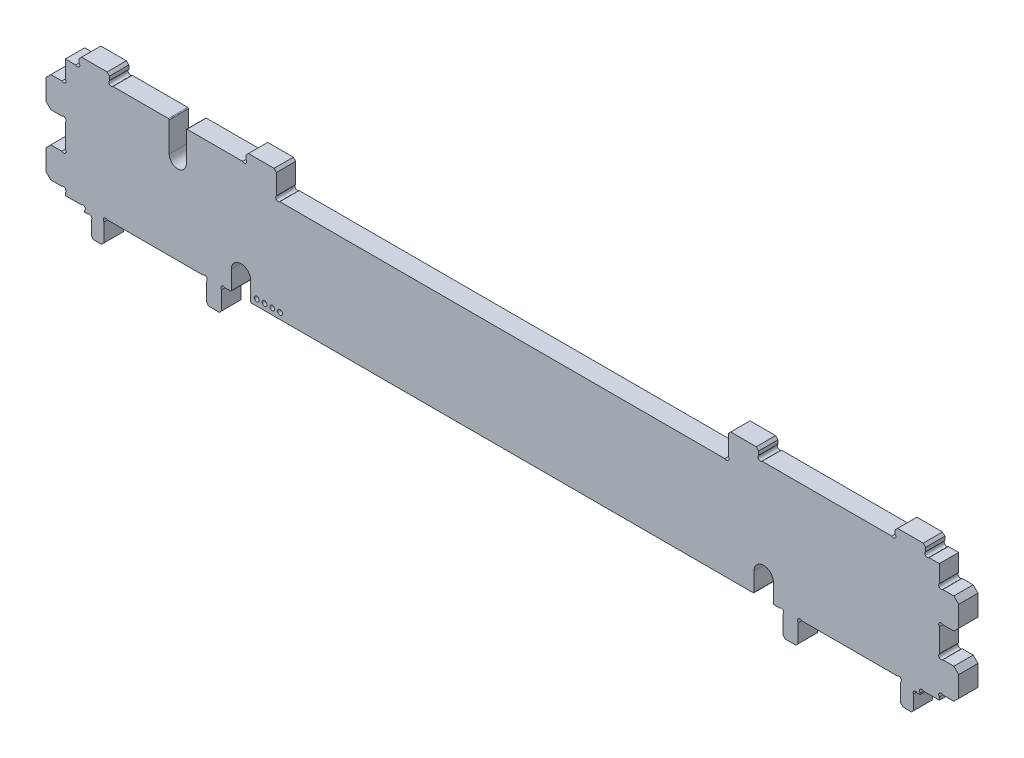
SolidWorks part; units mm, degrees
material "PVC Rigid"
ref_plane "Front Plane" through (0, 0, 0) normal (0, 0, 1) x (1, 0, 0)
ref_plane "Top Plane" through (0, 0, 0) normal (0, 1, 0) x (1, 0, 0)
ref_plane "Right Plane" through (0, 0, 0) normal (1, 0, 0) x (0, 0, -1)
sketch "Model" plane through (0, 0, 0) normal (0, 0, 1) x (1, 0, 0)
  line L0 (138.1552, -67.6125) -> (138.949, -66.8188)
  line L1 (134.6215, -66.8188) -> (135.4153, -67.6125)
  line L2 (100.1328, -67.6125) -> (100.9265, -66.8188)
  line L3 (95.9265, -66.8188) -> (96.7203, -67.6125)
  line L4 (-89.3772, -67.6125) -> (-88.5835, -66.8188)
  line L5 (-93.5835, -66.8188) -> (-92.7897, -67.6125)
  line L6 (-128.0722, -67.6125) -> (-127.2785, -66.8188)
  line L7 (-131.5077, -66.8188) -> (-130.7139, -67.6125)
  line L8 (-146.3285, -56.025) -> (-144.741, -57.6125)
  line L9 (-144.741, -47.6125) -> (-146.3285, -49.2)
  line L10 (-146.3285, -36.025) -> (-144.741, -37.6125)
  line L11 (-144.741, -27.6125) -> (-146.3285, -29.2)
  line L12 (-134.6597, -17.6125) -> (-135.4535, -18.4063)
  line L13 (-125.4535, -18.4063) -> (-126.2472, -17.6125)
  line L14 (-79.7957, -17.6125) -> (-80.5895, -18.4063)
  line L15 (-70.5895, -18.4063) -> (-71.3832, -17.6125)
  line L16 (-69.4669, -26.1597) -> (76.81, -26.1597)
  line L17 (78.7263, -17.6125) -> (77.9325, -18.4063)
  line L18 (87.9325, -18.4063) -> (87.1388, -17.6125)
  line L19 (133.5903, -17.6125) -> (132.7965, -18.4063)
  line L20 (142.7965, -18.4063) -> (142.0028, -17.6125)
  line L21 (153.6715, -29.2) -> (152.084, -27.6125)
  line L22 (152.084, -37.6125) -> (153.6715, -36.025)
  line L23 (153.6715, -49.2) -> (152.084, -47.6125)
  line L24 (152.084, -57.6125) -> (153.6715, -56.025)
  line L25 (102.0491, -59.6877) -> (133.499, -59.6877)
  line L26 (100.9265, -66.8188) -> (100.9265, -60.8103)
  line L27 (96.7203, -67.6125) -> (100.1328, -67.6125)
  line L28 (95.9265, -60.8103) -> (95.9265, -66.8188)
  line L29 (-87.4609, -59.6877) -> (94.804, -59.6877)
  line L30 (-88.5835, -66.8188) -> (-88.5835, -60.8103)
  line L31 (-92.7897, -67.6125) -> (-89.3772, -67.6125)
  line L32 (-93.5835, -60.8103) -> (-93.5835, -66.8188)
  line L33 (-126.1559, -59.6877) -> (-94.706, -59.6877)
  line L34 (-127.2785, -66.8188) -> (-127.2785, -60.8103)
  line L35 (-130.7139, -67.6125) -> (-128.0722, -67.6125)
  line L36 (-131.5077, -62.3851) -> (-131.5077, -66.8188)
  line L37 (-133.6285, -61.2625) -> (-132.6302, -61.2625)
  line L38 (-133.6285, -60.8103) -> (-133.6285, -61.2625)
  line L39 (-139.9785, -59.6877) -> (-134.751, -59.6877)
  line L40 (-139.9785, -58.7351) -> (-139.9785, -59.6877)
  line L41 (-144.741, -57.6125) -> (-141.101, -57.6125)
  line L42 (-146.3285, -49.2) -> (-146.3285, -56.025)
  line L43 (-141.101, -47.6125) -> (-144.741, -47.6125)
  line L44 (-139.9785, -38.7351) -> (-139.9785, -46.49)
  line L45 (-144.741, -37.6125) -> (-141.101, -37.6125)
  line L46 (-146.3285, -29.2) -> (-146.3285, -36.025)
  line L47 (-141.101, -27.6125) -> (-144.741, -27.6125)
  line L48 (-139.9785, -20.7875) -> (-139.9785, -26.49)
  line L49 (-136.576, -20.7875) -> (-139.9785, -20.7875)
  line L50 (-135.4535, -18.4063) -> (-135.4535, -19.665)
  line L51 (-126.2472, -17.6125) -> (-134.6597, -17.6125)
  line L52 (-125.4535, -19.665) -> (-125.4535, -18.4063)
  line L53 (-105.5215, -20.7875) -> (-124.3309, -20.7875)
  line L54 (-105.5215, -29.665) -> (-105.5215, -20.7875)
  line L55 (-101.644, -30.7875) -> (-104.3989, -30.7875)
  line L56 (-100.5215, -20.7875) -> (-100.5215, -29.665)
  line L57 (-81.712, -20.7875) -> (-100.5215, -20.7875)
  line L58 (-80.5895, -18.4063) -> (-80.5895, -19.665)
  line L59 (-71.3832, -17.6125) -> (-79.7957, -17.6125)
  line L60 (-70.5895, -25.0372) -> (-70.5895, -18.4063)
  line L61 (77.9325, -18.4063) -> (77.9325, -25.0372)
  line L62 (87.1388, -17.6125) -> (78.7263, -17.6125)
  line L63 (87.9325, -19.665) -> (87.9325, -18.4063)
  line L64 (131.674, -20.7875) -> (89.0551, -20.7875)
  line L65 (132.7965, -18.4063) -> (132.7965, -19.665)
  line L66 (142.0028, -17.6125) -> (133.5903, -17.6125)
  line L67 (142.7965, -19.665) -> (142.7965, -18.4063)
  line L68 (147.3215, -20.7875) -> (143.9191, -20.7875)
  line L69 (147.3215, -26.49) -> (147.3215, -20.7875)
  line L70 (152.084, -27.6125) -> (148.4441, -27.6125)
  line L71 (153.6715, -36.025) -> (153.6715, -29.2)
  line L72 (148.4441, -37.6125) -> (152.084, -37.6125)
  line L73 (147.3215, -46.49) -> (147.3215, -38.7351)
  line L74 (152.084, -47.6125) -> (148.4441, -47.6125)
  line L75 (153.6715, -56.025) -> (153.6715, -49.2)
  line L76 (148.4441, -57.6125) -> (152.084, -57.6125)
  line L77 (147.3215, -59.6877) -> (147.3215, -58.7351)
  line L78 (142.0941, -59.6877) -> (147.3215, -59.6877)
  line L79 (140.9715, -61.2625) -> (140.9715, -60.8103)
  line L80 (140.0715, -61.2625) -> (140.9715, -61.2625)
  line L81 (138.949, -66.8188) -> (138.949, -62.3851)
  line L82 (135.4153, -67.6125) -> (138.1552, -67.6125)
  line L83 (134.6215, -60.8103) -> (134.6215, -66.8188)
  arc A0 (-70.5895, -25.0372) -> (-69.4669, -26.1597) centre (-70.0282, -25.5985) ccw
  arc A1 (76.81, -26.1597) -> (77.9325, -25.0372) centre (77.3713, -25.5985) ccw
  arc A2 (102.0491, -59.6877) -> (100.9265, -60.8103) centre (101.4878, -60.249) ccw
  arc A3 (95.9265, -60.8103) -> (94.804, -59.6877) centre (95.3653, -60.249) ccw
  arc A4 (-87.4609, -59.6877) -> (-88.5835, -60.8103) centre (-88.0222, -60.249) ccw
  arc A5 (-93.5835, -60.8103) -> (-94.706, -59.6877) centre (-94.1447, -60.249) ccw
  arc A6 (-126.1559, -59.6877) -> (-127.2785, -60.8103) centre (-126.7172, -60.249) ccw
  arc A7 (-131.5077, -62.3851) -> (-132.6302, -61.2625) centre (-132.069, -61.8238) ccw
  arc A8 (-133.6285, -60.8103) -> (-134.751, -59.6877) centre (-134.1897, -60.249) ccw
  arc A9 (-139.9785, -58.7351) -> (-141.101, -57.6125) centre (-140.5397, -58.1738) ccw
  arc A10 (-141.101, -47.6125) -> (-139.9785, -46.49) centre (-140.5397, -47.0513) ccw
  arc A11 (-139.9785, -38.7351) -> (-141.101, -37.6125) centre (-140.5397, -38.1738) ccw
  arc A12 (-141.101, -27.6125) -> (-139.9785, -26.49) centre (-140.5397, -27.0513) ccw
  arc A13 (-136.576, -20.7875) -> (-135.4535, -19.665) centre (-136.0147, -20.2263) ccw
  arc A14 (-125.4535, -19.665) -> (-124.3309, -20.7875) centre (-124.8922, -20.2263) ccw
  arc A15 (-105.5215, -29.665) -> (-104.3989, -30.7875) centre (-104.9602, -30.2263) ccw
  arc A16 (-101.644, -30.7875) -> (-100.5215, -29.665) centre (-101.0827, -30.2263) ccw
  arc A17 (-81.712, -20.7875) -> (-80.5895, -19.665) centre (-81.1507, -20.2263) ccw
  arc A18 (87.9325, -19.665) -> (89.0551, -20.7875) centre (88.4938, -20.2263) ccw
  arc A19 (131.674, -20.7875) -> (132.7965, -19.665) centre (132.2353, -20.2263) ccw
  arc A20 (142.7965, -19.665) -> (143.9191, -20.7875) centre (143.3578, -20.2263) ccw
  arc A21 (147.3215, -26.49) -> (148.4441, -27.6125) centre (147.8828, -27.0513) ccw
  arc A22 (148.4441, -37.6125) -> (147.3215, -38.7351) centre (147.8828, -38.1738) ccw
  arc A23 (147.3215, -46.49) -> (148.4441, -47.6125) centre (147.8828, -47.0513) ccw
  arc A24 (148.4441, -57.6125) -> (147.3215, -58.7351) centre (147.8828, -58.1738) ccw
  arc A25 (142.0941, -59.6877) -> (140.9715, -60.8103) centre (141.5328, -60.249) ccw
  arc A26 (140.0715, -61.2625) -> (138.949, -62.3851) centre (139.5102, -61.8238) ccw
  arc A27 (134.6215, -60.8103) -> (133.499, -59.6877) centre (134.0603, -60.249) ccw
extrude "Boss-Extrude1" add sketch "Model" along normal blind 6.35
sketch "Sketch3" plane through (0, 0, 6.35) normal (0, 0, 1) x (1, 0, 0)
  line L0 (-131.3553, -62.1713) -> (-131.3553, -66.9712)
  line L1 (-131.5077, -66.8188) -> (-130.7139, -67.6125) construction
  line L2 (-131.5077, -62.3851) -> (-131.5077, -66.8188) construction
  line L3 (-131.5077, -62.3851) -> (-131.5077, -66.8188)
  line L4 (-131.5077, -66.8188) -> (-131.3553, -66.9712)
  line L5 (138.7966, -62.1713) -> (138.7966, -66.9712)
  line L7 (138.1552, -67.6125) -> (138.949, -66.8188) construction
  line L8 (138.949, -66.8188) -> (138.949, -62.3851) construction
  line L9 (138.7966, -66.9712) -> (138.949, -66.8188)
  line L10 (138.949, -66.8188) -> (138.949, -62.3851)
  arc A0 (-131.5077, -62.3851) -> (-132.6302, -61.2625) centre (-132.069, -61.8238) ccw construction
  arc A1 (-131.5077, -62.3851) -> (-131.3553, -62.1713) centre (-132.069, -61.8238) ccw
  arc A4 (140.0715, -61.2625) -> (138.949, -62.3851) centre (139.5102, -61.8238) ccw construction
  arc A5 (138.7966, -62.1713) -> (138.949, -62.3851) centre (139.5102, -61.8238) ccw
  dimension "D1" = 0.1524
  dimension "D2" = 0.1524
extrude "Cut-Extrude2" cut sketch "Sketch3" against normal through all
sketch "Sketch4" plane through (0, 0, 6.35) normal (0, 0, 1) x (1, 0, 0)
  line L0 (-87.4609, -59.6877) -> (94.804, -59.6877) construction
  line L1 (-85.4085, -59.6877) -> (-79.0585, -59.6877)
  line L2 (-85.4085, -59.6877) -> (-85.4085, -53.3377)
  line L4 (-79.0585, -59.6877) -> (-79.0585, -53.3377)
  line L5 (-88.5835, -66.8188) -> (-88.5835, -60.8103) construction
  line L6 (-139.9785, -20.7875) -> (147.3215, -59.6877) construction
  line L7 (3.6715, -54.3155) -> (3.6715, -26.1597) construction
  line L8 (76.81, -26.1597) -> (-69.4669, -26.1597) construction
  line L9 (86.4015, -59.6877) -> (86.4015, -53.3377)
  line L10 (92.7515, -59.6877) -> (92.7515, -53.3377)
  line L11 (92.7515, -59.6877) -> (86.4015, -59.6877)
  arc A0 (-79.0585, -53.3377) -> (-85.4085, -53.3377) centre (-82.2335, -53.3377) ccw
  arc A1 (86.4015, -53.3377) -> (92.7515, -53.3377) centre (89.5765, -53.3377) cw
  point P19 (3.6715, -40.2376)
  dimension "D2" = 6.35
  dimension "D1" = 3.175
  dimension "D3" = 6.35
  dimension "D4" = 6.35
extrude "Cut-Extrude3" cut sketch "Sketch4" against normal through all
sketch "Sketch6" plane through (0, 0, 6.35) normal (0, 0, 1) x (1, 0, 0)
  line L0 (-101.644, -30.7875) -> (-104.3989, -30.7875) construction
  line L1 (-81.712, -20.7875) -> (-100.5215, -20.7875) construction
  line L3 (-105.8335, -30.7875) -> (-105.8335, -20.7875)
  line L4 (-105.8335, -20.7875) -> (-100.2094, -20.7875)
  line L5 (-100.2094, -30.7875) -> (-100.2094, -20.7875)
  arc A0 (-105.8335, -30.7875) -> (-100.2094, -30.7875) centre (-103.0215, -30.7875) ccw
  arc A1 (-101.644, -30.7875) -> (-100.5215, -29.665) centre (-101.0827, -30.2263) ccw construction
extrude "Cut-Extrude4" cut sketch "Sketch6" against normal through all
fillet "Fillet1" radius 0.254 6 edges at (86.4015, -59.6877, 3.175) (92.7515, -59.6877, 3.175) (-79.0585, -59.6877, 3.175) (-85.4085, -59.6877, 3.175) (-105.8335, -20.7875, 3.175) (-100.2094, -20.7875, 3.175)
sketch "Sketch7" plane through (0, 0, 6.35) normal (0, 0, 1) x (1, 0, 0)
  line L0 (-79.0585, -59.4337) -> (-79.0585, -53.3377) construction
  line L1 (-78.8045, -59.6877) -> (86.1475, -59.6877) construction
  circle A0 centre (-77.0265, -57.6557) radius 0.7937
  dimension "D1" = 1.5875
  dimension "D2" = 2.032
  dimension "D3" = 2.032
extrude "Cut-Extrude5" cut sketch "Sketch7" against normal blind 2.54
pattern_linear "LPattern1" count 4 spacing 2.54 along (1, 0, 0) of "Cut-Extrude5"
